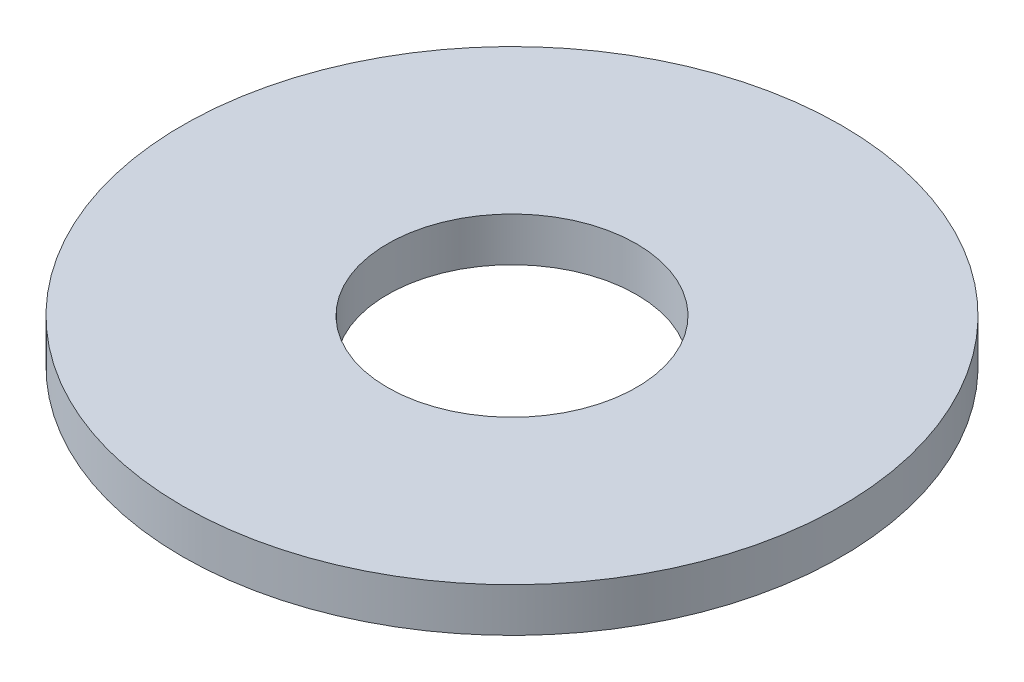
SolidWorks part; units mm, degrees
ref_plane "前基準面" through (0, 0, 0) normal (0, 0, 1) x (1, 0, 0)
ref_plane "上基準面" through (0, 0, 0) normal (0, 1, 0) x (1, 0, 0)
ref_plane "右基準面" through (0, 0, 0) normal (1, 0, 0) x (0, 0, -1)
sketch "草圖1" plane through (0, 0, 0) normal (0, 1, 0) x (1, 0, 0)
  circle A0 centre (0, 0) radius 11.25
  circle A1 centre (0, 0) radius 4.25
  dimension "D1" = 22.5
  dimension "D2" = 8.5
extrude "填料-伸長1" add sketch "草圖1" along normal blind 1.5
